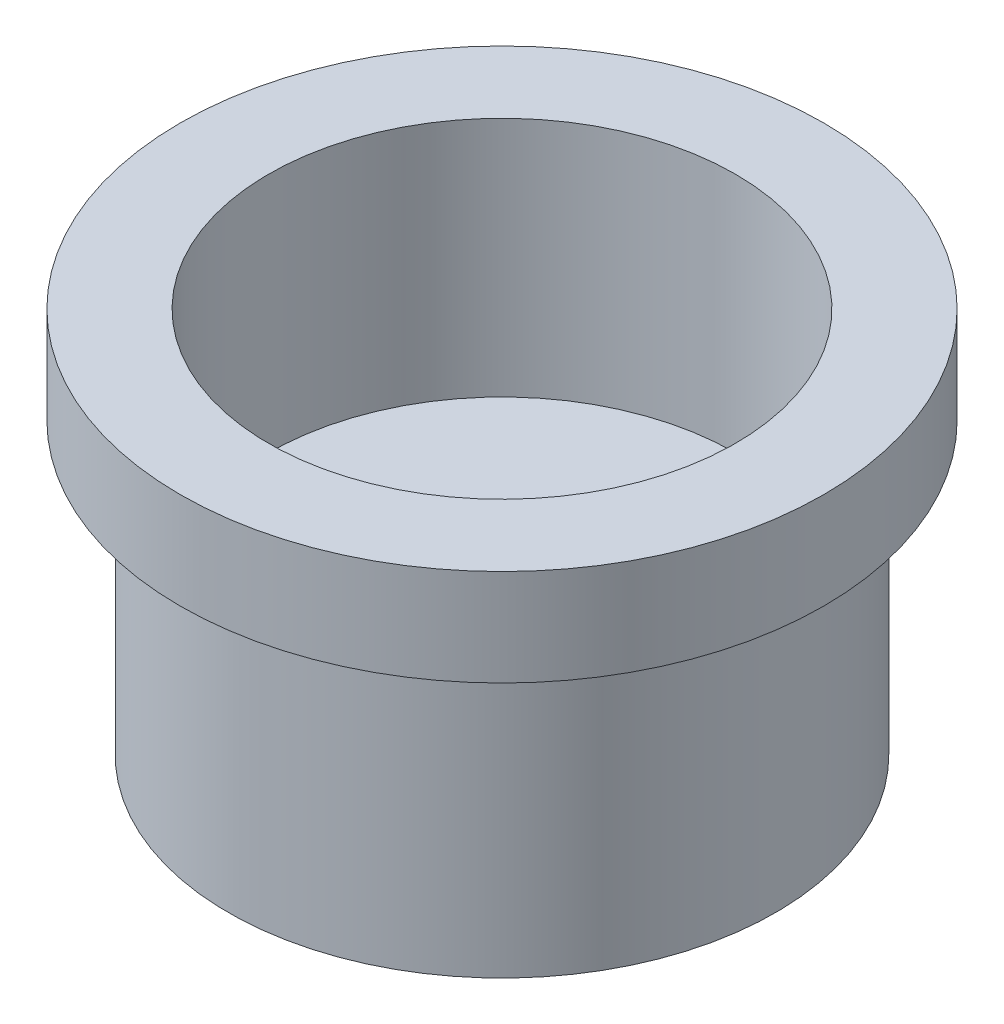
SolidWorks part; units mm, degrees
ref_plane "前视基准面" through (0, 0, 0) normal (0, 0, 1) x (1, 0, 0)
ref_plane "上视基准面" through (0, 0, 0) normal (0, 1, 0) x (1, 0, 0)
ref_plane "右视基准面" through (0, 0, 0) normal (1, 0, 0) x (0, 0, -1)
sketch "草图1" plane through (0, 0, 0) normal (0, 0, 1) x (1, 0, 0)
  line L0 (0, 0) -> (-4.4767, 0) construction
  line L1 (0, 0) -> (0, 28.0423) construction
  line L2 (-2.5, 0) -> (-2.5, 11)
  line L3 (-2.5, 11) -> (-4.75, 11)
  line L4 (-4.75, 11) -> (-4.75, 15)
  line L5 (-4.75, 15) -> (-14.5, 15)
  line L6 (-14.5, 15) -> (-14.5, 30)
  line L7 (-14.5, 30) -> (-20, 30)
  line L8 (-20, 30) -> (-20, 24)
  line L9 (-20, 24) -> (-17, 24)
  line L10 (-17, 24) -> (-17, 6)
  line L11 (-17, 6) -> (-6.5, 6)
  line L12 (-6.5, 6) -> (-6.5, 5)
  line L13 (-6.5, 5) -> (-4.5, 5)
  line L14 (-4.5, 5) -> (-4.5, 0)
  line L15 (-4.5, 0) -> (-2.5, 0)
  point P6 (0, 28.0423)
  dimension "D1" = 5
  dimension "D2" = 9
  dimension "D3" = 2
  dimension "D4" = 6
  dimension "D5" = 6
  dimension "D6" = 9.5
  dimension "D7" = 4
  dimension "D8" = 1
  dimension "D9" = 34
  dimension "D10" = 40
  dimension "D11" = 6
  dimension "D12" = 29
  dimension "D13" = 15
revolve "旋转1" add sketch "草图1" angle 360 about L1
